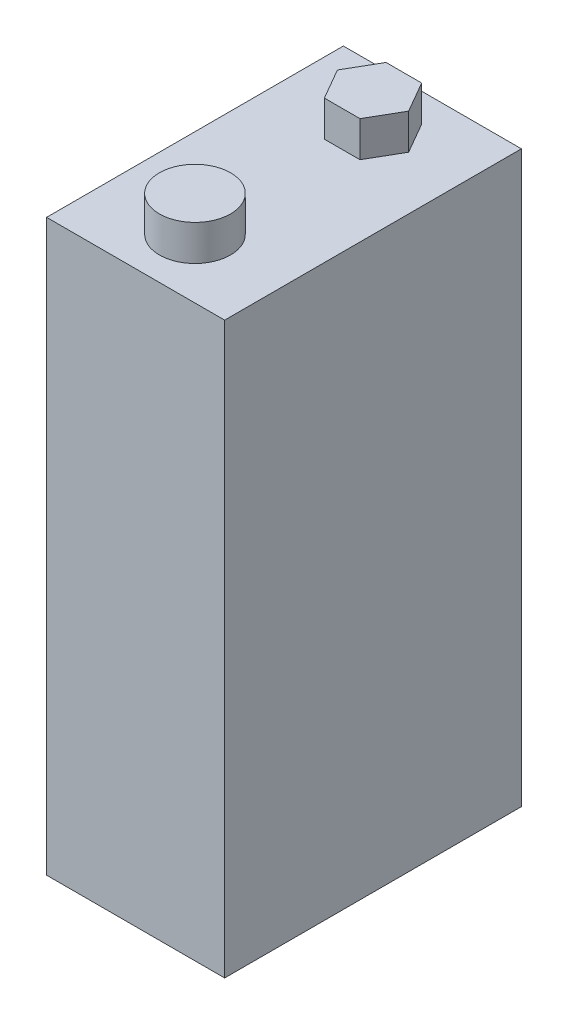
SolidWorks part; units mm, degrees
ref_plane "Front Plane" through (0, 0, 0) normal (0, 0, 1) x (1, 0, 0)
ref_plane "Top Plane" through (0, 0, 0) normal (0, 1, 0) x (1, 0, 0)
ref_plane "Right Plane" through (0, 0, 0) normal (1, 0, 0) x (0, 0, -1)
sketch "Sketch1" plane through (0, 0, 0) normal (1, 0, 0) x (0, 0, -1)
  line L1 (0, 0) -> (25, 0)
  line L2 (0, 0) -> (0, -48)
  line L3 (0, -48) -> (25, -48)
  line L4 (25, 0) -> (25, -48)
  dimension "D1" = 48
  dimension "D2" = 25
extrude "Boss-Extrude1" add sketch "Sketch1" along normal blind 15
sketch "Sketch2" plane through (0, 0, 0) normal (0, 1, 0) x (1, 0, 0)
  line L0 (7.5, 5) -> (7.5, 20) construction
  line L3 (0, 12.5) -> (15, 12.5) construction
  line L4 (0, 25) -> (0, 0) construction
  line L5 (15, 25) -> (15, 0) construction
  line L7 (4.5, 20) -> (6, 17.4019)
  line L8 (6, 17.4019) -> (9, 17.4019)
  line L9 (9, 17.4019) -> (10.5, 20)
  line L10 (10.5, 20) -> (9, 22.5981)
  line L11 (9, 22.5981) -> (6, 22.5981)
  line L12 (6, 22.5981) -> (4.5, 20)
  circle A0 centre (7.5, 5) radius 3
  circle A1 centre (7.5, 20) radius 2.5981 construction
  point P3 (7.5, 12.5)
extrude "Boss-Extrude2" add sketch "Sketch2" along normal blind 3
